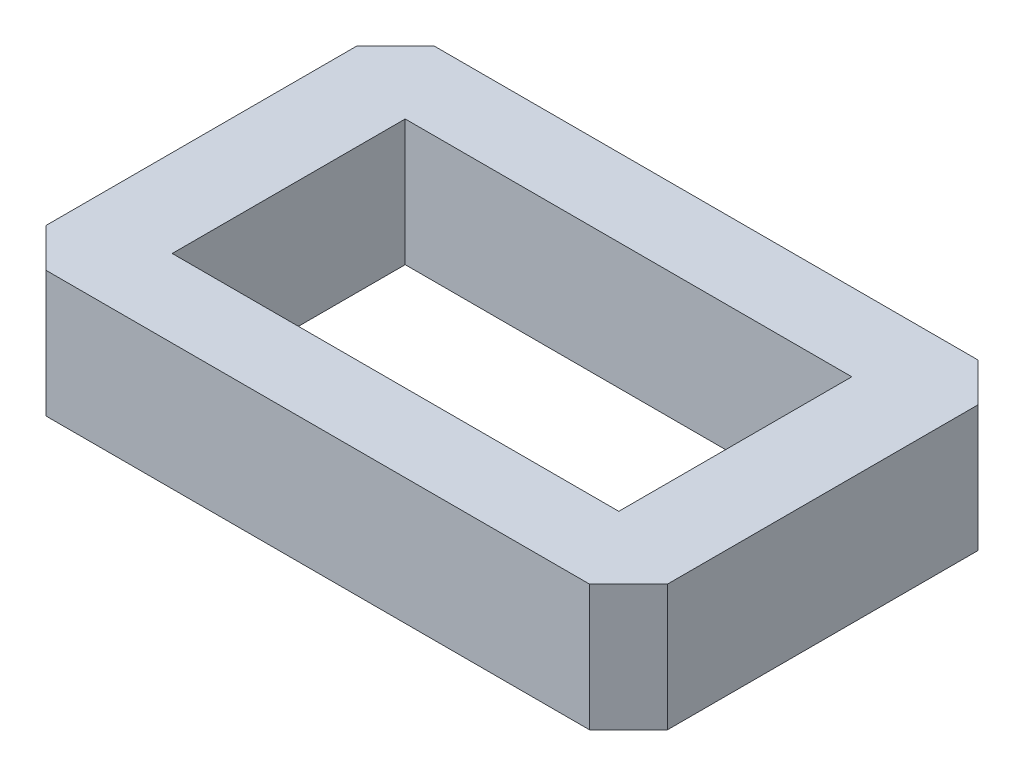
SolidWorks part; units mm, degrees
ref_plane "Front Plane" through (0, 0, 0) normal (0, 0, 1) x (1, 0, 0)
ref_plane "Top Plane" through (0, 0, 0) normal (0, 1, 0) x (1, 0, 0)
ref_plane "Right Plane" through (0, 0, 0) normal (1, 0, 0) x (0, 0, -1)
sketch "Sketch1" plane through (0, 0, 0) normal (0, 1, 0) x (1, 0, 0)
  line L1 (0, 0) -> (32, 0)
  line L2 (0, 0) -> (0, 20)
  line L3 (0, 20) -> (32, 20)
  line L4 (32, 0) -> (32, 20)
  dimension "D1" = 20
  dimension "D2" = 32
extrude "Boss-Extrude1" add sketch "Sketch1" along normal blind 6.5
sketch "Sketch2" plane through (0, 6.5, 0) normal (0, 1, 0) x (1, 0, 0)
  line L0 (16, 20) -> (16, 0) construction
  line L1 (32, 20) -> (0, 20) construction
  line L2 (0, 0) -> (32, 0) construction
  line L4 (4.5, 4) -> (27.5, 4)
  line L5 (4.5, 4) -> (4.5, 16)
  line L6 (4.5, 16) -> (27.5, 16)
  line L7 (27.5, 4) -> (27.5, 16)
  line L8 (4.5, 4) -> (27.5, 16) construction
  line L9 (4.5, 16) -> (27.5, 4) construction
  point P6 (16, 10)
  dimension "D1" = 12
  dimension "D2" = 23
extrude "Cut-Extrude1" cut sketch "Sketch2" against normal through all
chamfer "Chamfer1" distance 2 angle 45 4 edges at (0, 3.25, 0) (0, 3.25, -20) (32, 3.25, -20) (32, 3.25, 0)
